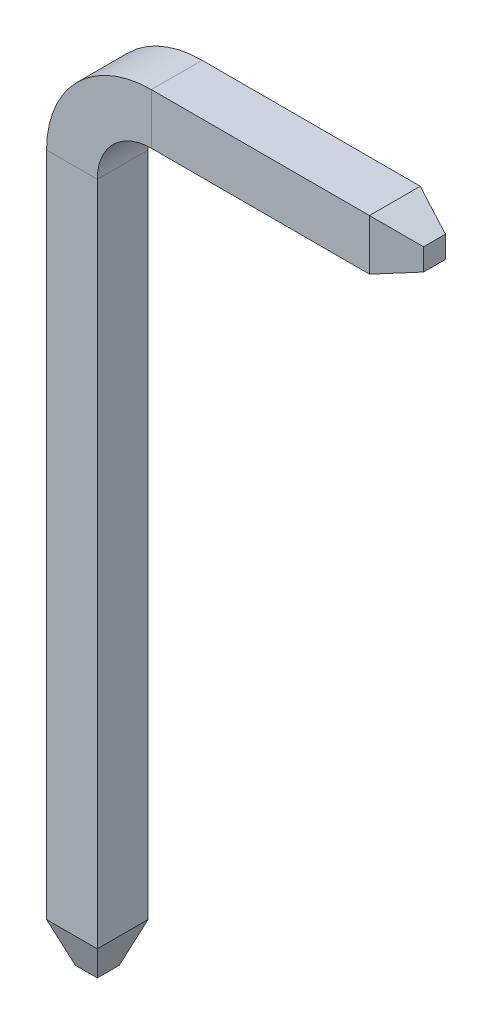
SolidWorks part; units mm, degrees
ref_plane "Спереди" through (0, 0, 0) normal (0, 0, 1) x (1, 0, 0)
ref_plane "Сверху" through (0, 0, 0) normal (0, 1, 0) x (1, 0, 0)
ref_plane "Справа" through (0, 0, 0) normal (1, 0, 0) x (0, 0, -1)
sketch "Эскиз3" plane through (0, 0, 0) normal (0, 1, 0) x (1, 0, 0)
  line L1 (-1.25, 1.25) -> (1.25, 1.25) construction
  line L2 (-1.25, 1.25) -> (-1.25, -1.25) construction
  line L3 (-1.25, -1.25) -> (1.25, -1.25) construction
  line L4 (1.25, 1.25) -> (1.25, -1.25) construction
  line L5 (-1.25, 1.25) -> (1.25, -1.25) construction
  line L6 (-1.25, -1.25) -> (1.25, 1.25) construction
  point P0 (0, 0)
  dimension "D1" = 2.5
sketch "Эскиз4" plane through (0, 0, 0) normal (0, 0, 1) x (1, 0, 0)
  line L0 (-1.25, 1.25) -> (1.25, 1.25) construction
  line L1 (-1.25, 1.25) -> (-1.25, -1.25) construction
  line L2 (-1.25, -1.25) -> (1.25, -1.25) construction
  line L3 (1.25, 1.25) -> (1.25, -1.25) construction
  line L4 (-1.25, 1.25) -> (1.25, -1.25) construction
  line L5 (-1.25, -1.25) -> (1.25, 1.25) construction
  point P0 (0, 0)
  dimension "D1" = 2.5
sketch "Эскиз1" plane through (0, 0, 0) normal (0, 1, 0) x (1, 0, 0)
  line L1 (-0.32, 0.32) -> (0.32, 0.32)
  line L2 (-0.32, 0.32) -> (-0.32, -0.32)
  line L3 (-0.32, -0.32) -> (0.32, -0.32)
  line L4 (0.32, 0.32) -> (0.32, -0.32)
  line L5 (-0.32, 0.32) -> (0.32, -0.32) construction
  line L6 (-0.32, -0.32) -> (0.32, 0.32) construction
  point P0 (0, 0)
  dimension "D1" = 0.64
sketch "Эскиз2" plane through (0, 0, 0) normal (0, 0, 1) x (1, 0, 0)
  line L0 (0, 0) -> (0, 1.65)
  line L1 (1, 2.65) -> (4.25, 2.65)
  line L3 (0, 0) -> (0, -7.25)
  line L4 (1.25, 1.25) -> (1.25, -1.25) construction
  line L6 (-1.25, -1.25) -> (1.25, -1.25) construction
  arc A0 (0, 1.65) -> (1, 2.65) centre (1, 1.65) cw
  dimension "D4" = 1
  dimension "D1" = 3
  dimension "D2" = 3.9
  dimension "D3" = 6
sweep "По траектории1" add profiles "Эскиз1" path "Эскиз2"
chamfer "Фаска1" distance 0.5 angle 20 4 edges at (4.25, 2.65, 0.32) (4.25, 2.97, 0) (4.25, 2.65, -0.32) (4.25, 2.33, 0)
chamfer "Фаска2" distance 0.5 angle 20 4 edges at (0, -7.25, -0.32) (-0.32, -7.25, 0) (0, -7.25, 0.32) (0.32, -7.25, 0)
sketch "Эскиз5" plane through (0, 0, 0) normal (0, 0, 1) x (1, 0, 0)
  line L0 (0, -8.1573) -> (0, 6.6577) construction
  line L2 (-2.4103, 2.65) -> (5.9307, 2.65) construction
  line L3 (4.25, 2.788) -> (4.25, 2.512) construction
  point P7 (4.25, 2.65)
